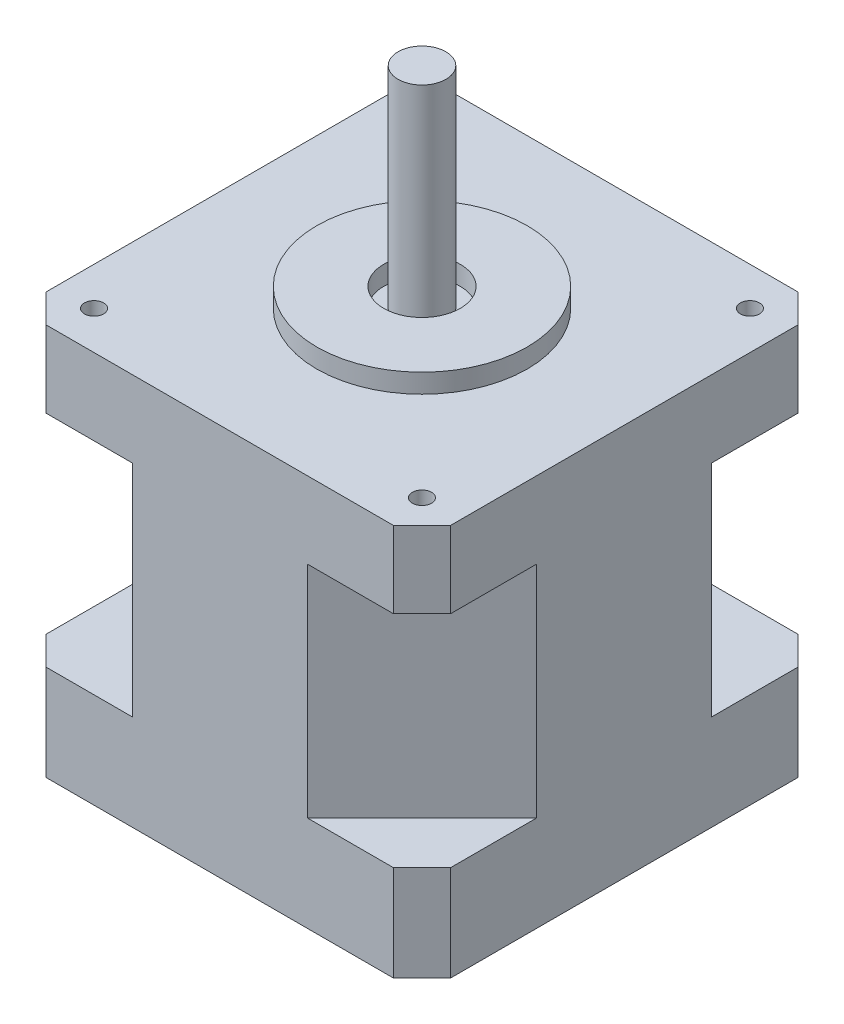
SolidWorks part; units mm, degrees
ref_plane "Front Plane" through (0, 0, 0) normal (0, 0, 1) x (1, 0, 0)
ref_plane "Top Plane" through (0, 0, 0) normal (0, 1, 0) x (1, 0, 0)
ref_plane "Right Plane" through (0, 0, 0) normal (1, 0, 0) x (0, 0, -1)
sketch "Sketch1" plane through (0, 0, 0) normal (0, 1, 0) x (1, 0, 0)
  line L0 (-18.15, 21.15) -> (-21.15, 18.15)
  line L1 (18.15, 21.15) -> (-18.15, 21.15)
  line L2 (21.15, 18.15) -> (21.15, -18.15)
  line L3 (18.15, -21.15) -> (-18.15, -21.15)
  line L4 (-21.15, 18.15) -> (-21.15, -18.15)
  line L5 (21.15, 21.15) -> (-21.15, -21.15) construction
  line L6 (21.15, -21.15) -> (-21.15, 21.15) construction
  line L7 (21.15, 18.15) -> (18.15, 21.15)
  line L8 (21.15, -18.15) -> (18.15, -21.15)
  line L9 (-18.15, -21.15) -> (-21.15, -18.15)
  point P0 (0, 0)
  dimension "D1" = 42.3
  dimension "D2" = 42.3
extrude "Boss-Extrude1" add sketch "Sketch1" against normal blind 8 from offset 22 offset against normal yes
sketch "Sketch2" plane through (0, -30, 0) normal (0, -1, 0) x (-1, 0, 0)
  line L0 (-21.15, 9.15) -> (-9.15, 21.15)
  line L1 (-9.15, -21.15) -> (9.15, -21.15)
  line L2 (-21.15, -9.15) -> (-21.15, 9.15)
  line L3 (-9.15, 21.15) -> (9.15, 21.15)
  line L4 (21.15, -9.15) -> (21.15, 9.15)
  line L5 (-21.15, -21.15) -> (21.15, 21.15) construction
  line L6 (-21.15, 21.15) -> (21.15, -21.15) construction
  line L7 (9.15, 21.15) -> (21.15, 9.15)
  line L8 (9.15, -21.15) -> (21.15, -9.15)
  line L9 (-21.15, -9.15) -> (-9.15, -21.15)
  point P0 (0, 0)
  dimension "D1" = 42.3
  dimension "D2" = 42.3
extrude "Boss-Extrude3" add sketch "Sketch2" along normal blind 23
sketch "Sketch3" plane through (0, -53, 0) normal (0, -1, 0) x (-1, 0, 0)
  line L0 (-18.15, 21.15) -> (-21.15, 18.15)
  line L1 (18.15, 21.15) -> (-18.15, 21.15)
  line L2 (21.15, 18.15) -> (21.15, -18.15)
  line L3 (18.15, -21.15) -> (-18.15, -21.15)
  line L4 (-21.15, 18.15) -> (-21.15, -18.15)
  line L5 (21.15, 21.15) -> (-21.15, -21.15) construction
  line L6 (21.15, -21.15) -> (-21.15, 21.15) construction
  line L7 (21.15, 18.15) -> (18.15, 21.15)
  line L8 (21.15, -18.15) -> (18.15, -21.15)
  line L9 (-18.15, -21.15) -> (-21.15, -18.15)
  point P0 (0, 0)
extrude "Boss-Extrude4" add sketch "Sketch3" along normal blind 6
sketch "Sketch4" plane through (0, -22, 0) normal (0, 1, 0) x (-1, 0, 0)
  circle A0 centre (0, 0) radius 11
  circle A1 centre (0, 0) radius 4
  dimension "D1" = 22
  dimension "D2" = 7
extrude "Boss-Extrude5" add sketch "Sketch4" along normal blind 2
sketch "Sketch5" plane through (0, -22, 0) normal (0, 1, 0) x (-1, 0, 0)
  circle A0 centre (0, 0) radius 2.5
  dimension "D1" = 5
extrude "Boss-Extrude6" add sketch "Sketch5" along normal blind 22
hole_wizard "Ø2.0mm Dowel Hole1" positions "Sketch6" profile "Sketch7" hole size "Ø2.0" standard "ANSI Metric"
sketch "Sketch6" plane through (0, -22, 0) normal (0, 1, 0) x (1, 0, 0)
  line L0 (-21.15, 18.15) -> (-21.15, -18.15) construction
  line L1 (18.15, 21.15) -> (-18.15, 21.15) construction
  line L2 (18.15, -21.15) -> (-18.15, -21.15) construction
  line L3 (21.15, 18.15) -> (21.15, -18.15) construction
  point P0 (-17.15, 17.15)
  point P2 (-17.15, -17.15)
  point P4 (17.15, -17.15)
  point P6 (17.15, 17.15)
  point P13 (-17.15, -18.15)
  point P14 (18.15, 17.15)
  point P15 (12.9201, -10.7012)
  point P16 (-17.15, -17.049)
  point P21 (17.15, -17.15)
  dimension "D1" = 4
  dimension "D2" = 4
  dimension "D3" = 4
  dimension "D4" = 4
sketch "Sketch7" plane through (-17.15, -22, -17.15) normal (1, 0, 0) x (0, 0, 1)
  line L0 (0, 0) -> (0, 5.6009)
  line L1 (0, 5.6009) -> (1, 5)
  line L2 (1, 5) -> (1, 0)
  line L5 (1, 0) -> (0, 0)
  line L10 (0, 5.6009) -> (-1, 5) construction
  line L11 (0, -6.35) -> (0, 107.95) construction
  dimension "Hole Dia." = 2
  dimension "Hole Depth" = 5
  dimension "Drill Angle" = 118
sketch "Sketch8" plane through (0, -59, 0) normal (0, -1, 0) x (1, 0, 0)
  line L1 (-25.15, -8) -> (-21.15, -8)
  line L2 (-25.15, -8) -> (-25.15, 8)
  line L3 (-25.15, 8) -> (-21.15, 8)
  line L4 (-21.15, -8) -> (-21.15, 8)
  line L5 (-25.15, -8) -> (-21.15, 8) construction
  line L6 (-25.15, 8) -> (-21.15, -8) construction
  line L20 (18.15, -21.15) -> (21.15, -18.15)
  line L21 (21.15, -18.15) -> (21.15, 18.15)
  line L22 (21.15, 18.15) -> (18.15, 21.15)
  line L23 (18.15, 21.15) -> (-18.15, 21.15)
  line L24 (-18.15, 21.15) -> (-21.15, 18.15)
  line L25 (18.15, -21.15) -> (21.15, -18.15)
  line L26 (21.15, -18.15) -> (21.15, 18.15)
  line L27 (21.15, 18.15) -> (18.15, 21.15)
  line L28 (18.15, 21.15) -> (-18.15, 21.15)
  line L29 (-18.15, 21.15) -> (-21.15, 18.15)
  line L31 (-27.0761, 0) -> (28.7613, 0) construction
  line L34 (-18.15, -21.15) -> (18.15, -21.15)
  line L35 (-21.15, -18.15) -> (-18.15, -21.15)
  line L36 (-21.15, 18.15) -> (-21.15, -18.15)
  line L37 (-18.15, -21.15) -> (18.15, -21.15)
  line L38 (-21.15, -18.15) -> (-18.15, -21.15)
  line L39 (-21.15, 18.15) -> (-21.15, -18.15)
  circle A0 centre (0, 0) radius 5
  point P12 (-23.15, 0)
  line M11 (-18.15, -21.15) -> (18.15, -21.15)
  line M12 (18.15, -21.15) -> (21.15, -18.15)
  line M13 (21.15, -18.15) -> (21.15, 18.15)
  line M14 (21.15, 18.15) -> (18.15, 21.15)
  line M15 (18.15, 21.15) -> (-18.15, 21.15)
  line M16 (-18.15, 21.15) -> (-21.15, 18.15)
  line M17 (-21.15, 18.15) -> (-21.15, -18.15)
  line M18 (-21.15, -18.15) -> (-18.15, -21.15)
  dimension "D3" = 10
  dimension "D4" = 4
  dimension "D5" = 16
  dimension "D1" = 0
  dimension "D2" = 0
extrude "Boss-Extrude7" add sketch "Sketch8" along normal blind 4 contours A0 M18 M11 M12 M13 M14 M15 M16 M17 | L3 L2 L1 M17
